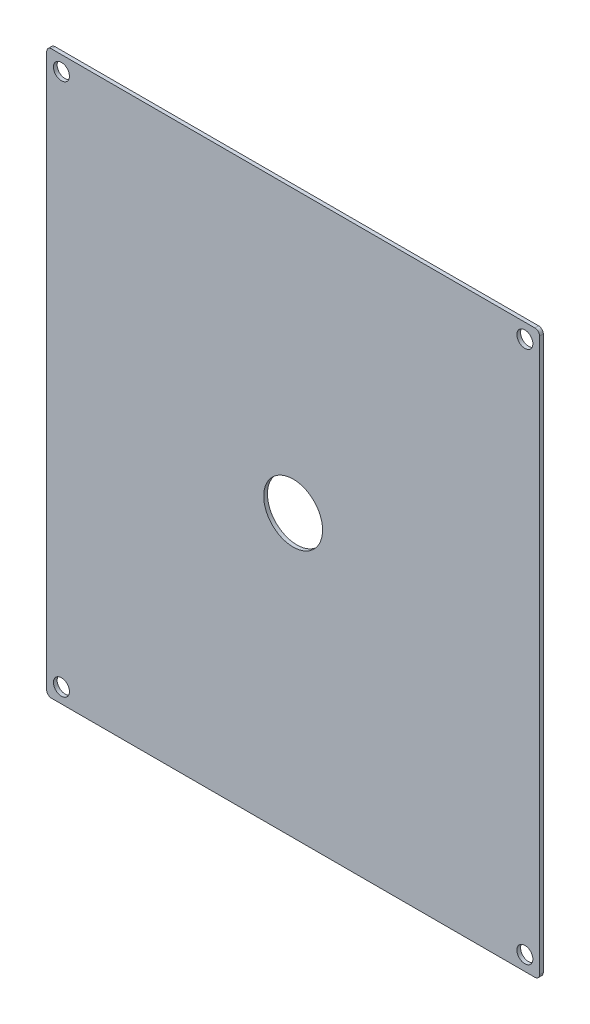
SolidWorks part; units mm, degrees
ref_plane "Front Plane" through (0, 0, 0) normal (0, 0, 1) x (1, 0, 0)
ref_plane "Top Plane" through (0, 0, 0) normal (0, 1, 0) x (1, 0, 0)
ref_plane "Right Plane" through (0, 0, 0) normal (1, 0, 0) x (0, 0, -1)
sketch "Sketch1" plane through (0, 0, 0) normal (0, 0, 1) x (1, 0, 0)
  line L1 (0, 0) -> (100, 0) construction
  line L2 (0, 0) -> (0, -115) construction
  line L3 (0, -115) -> (100, -115) construction
  line L4 (100, 0) -> (100, -115) construction
  line L5 (0, 0) -> (100, -115) construction
  line L6 (0, -115) -> (100, 0) construction
  line L7 (-3.175, 3.175) -> (103.175, 3.175)
  line L8 (-3.175, 3.175) -> (-3.175, -118.175)
  line L9 (-3.175, -118.175) -> (103.175, -118.175)
  line L10 (103.175, 3.175) -> (103.175, -118.175)
  line L11 (-3.175, 3.175) -> (103.175, -118.175) construction
  line L12 (-3.175, -118.175) -> (103.175, 3.175) construction
  circle A0 centre (0, 0) radius 1.725
  circle A1 centre (100, 0) radius 1.725
  circle A2 centre (100, -115) radius 1.725
  circle A3 centre (0, -115) radius 1.725
  circle A4 centre (50, -57.5) radius 6.35
  point P4 (50, -57.5)
  point P14 (50, -57.5)
  dimension "D3" = 3.45
  dimension "D8" = 12.7
  dimension "D1" = 100
  dimension "D2" = 115
  dimension "D4" = 3.175
  dimension "D5" = 3.175
  dimension "D6" = 3.175
  dimension "D7" = 3.175
extrude "Boss-Extrude1" add sketch "Sketch1" along normal blind 0.8
fillet "Fillet1" radius 1 4 edges at (-3.175, -118.175, 0.4) (103.175, -118.175, 0.4) (103.175, 3.175, 0.4) (-3.175, 3.175, 0.4)
